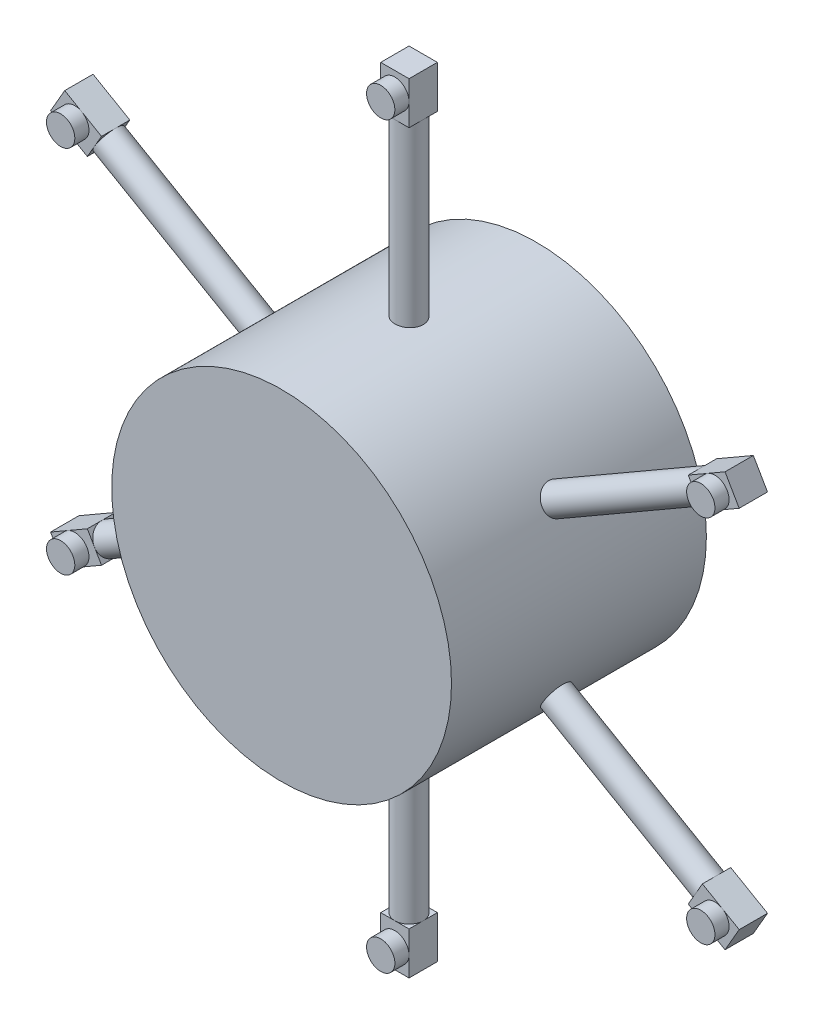
SolidWorks part; units mm, degrees
ref_plane "前基準面" through (0, 0, 0) normal (0, 0, 1) x (1, 0, 0)
ref_plane "上基準面" through (0, 0, 0) normal (0, 1, 0) x (1, 0, 0)
ref_plane "右基準面" through (0, 0, 0) normal (1, 0, 0) x (0, 0, -1)
sketch "草圖6" plane through (0, 0, 0) normal (0, 1, 0) x (1, 0, 0)
  circle A0 centre (0, 0) radius 5
  dimension "D1" = 10
sketch "草圖7" plane through (0, 0, 0) normal (0, 0, 1) x (1, 0, 0)
  line L0 (0, 0) -> (0, 130)
  dimension "D1" = 130
sweep "掃出1" add profiles "草圖6" path "草圖7"
sketch "草圖8" plane through (0, 0, 0) normal (0, -1, 0) x (1, 0, 0)
  line L0 (-5, -5) -> (5, 5) construction
  line L1 (-5, 5) -> (5, 5)
  line L2 (-5, 5) -> (-5, -5)
  line L3 (-5, -5) -> (5, -5)
  line L4 (5, 5) -> (5, -5)
  line L5 (-5, 5) -> (5, -5) construction
  point P4 (0, 0)
  dimension "D1" = 10
  dimension "D2" = 10
extrude "填料-伸長1" add sketch "草圖8" along normal mid plane 15
sketch "草圖9" plane through (0, 0, 5) normal (0, 0, 1) x (1, 0, 0)
  line L0 (5, -7.5) -> (-5, -7.5) construction
  line L1 (5, -7.5) -> (5, 7.5) construction
  circle A0 centre (0, -0.5) radius 5
  dimension "D1" = 10
  dimension "D2" = 7
  dimension "D3" = 5
extrude "填料-伸長2" add sketch "草圖9" along normal mid plane 10
sketch "草圖11" plane through (0, 0, 0) normal (0, 0, 1) x (1, 0, 0)
  line L0 (5, 130) -> (-5, 130) construction
  circle A0 centre (0, 130) radius 60
  dimension "D1" = 120
extrude "填料-伸長3" add sketch "草圖11" along normal mid plane 90
pattern_circular "環狀複製排列1" count 6 every 60 about axis through (0, 130, 0) along (0, 0, 1) of "掃出1", "填料-伸長1", "填料-伸長2"
